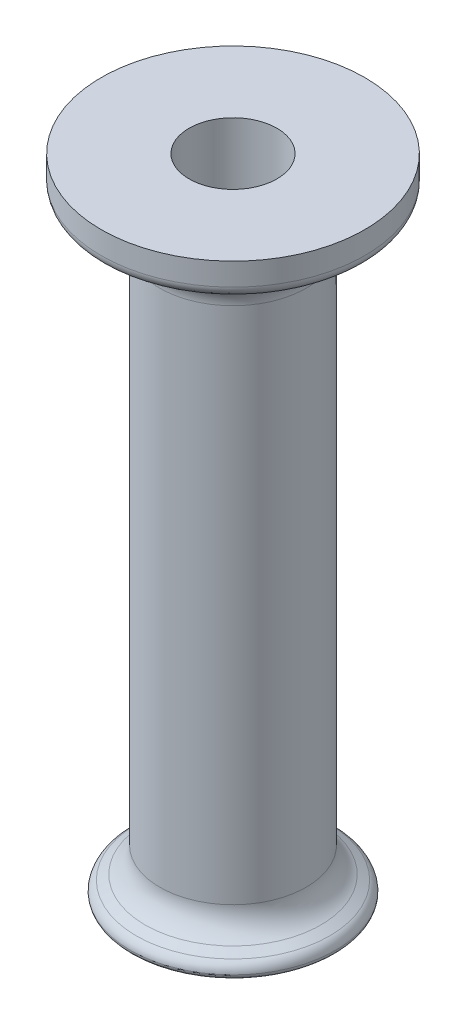
SolidWorks part; units mm, degrees
material "Natural Rubber"
ref_plane "Front Plane" through (0, 0, 0) normal (1, 0, 0) x (0, 1, 0)
ref_plane "Top Plane" through (0, 0, 0) normal (0, 0, 1) x (0, 1, 0)
ref_plane "Right Plane" through (0, 0, 0) normal (0, 1, 0) x (-1, 0, 0)
sketch "Sketch1" plane through (0, 0, 0) normal (1, 0, 0) x (0, 1, 0)
  line L0 (-16.1051, 0) -> (63.2397, 0) construction
  line L1 (0, 25.9687) -> (0, -12.1914) construction
  line L2 (0, 12.5) -> (41.3397, 12.5)
  line L3 (45.6699, 15) -> (50, 22.5)
  line L4 (50, 22.5) -> (55, 22.5)
  line L5 (55, 22.5) -> (55, 7.5)
  line L6 (-55, 7.5) -> (55, 7.5)
  line L7 (55, 0) -> (55, -0.9746)
  line L8 (-51.5566, 15) -> (-52.4226, 16.5)
  line L9 (-54.1547, 17.5) -> (-55, 17.5)
  line L10 (-55, 7.5) -> (-55, 17.5)
  line L11 (0, 12.5) -> (-47.2265, 12.5)
  arc A0 (41.3397, 12.5) -> (45.6699, 15) centre (41.3397, 17.5) ccw
  arc A1 (-47.2265, 12.5) -> (-51.5566, 15) centre (-47.2265, 17.5) cw
  arc A2 (-53.6374, 17.4319) -> (-55, 16.5) centre (-54, 16.5) ccw
  arc A3 (-52.4226, 16.5) -> (-54.1547, 17.5) centre (-54.1547, 15.5) ccw
  point P18 (0, 7.5)
  point P19 (0, 12.5)
  point P25 (-53, 17.5)
  dimension "D1" = 5
  dimension "D8" = 60
  dimension "D10" = 5
  dimension "D11" = 2
  dimension "D12" = 2
  dimension "D13" = 2
  dimension "D2" = 110
  dimension "D3" = 60
  dimension "D4" = 12.5
  dimension "D5" = 15
  dimension "D6" = 15
  dimension "D7" = 5
  dimension "D9" = 10
revolve "Revolve1" add sketch "Sketch1" angle 360 about L0
fillet "Fillet1" radius 2 1 edges at (0, 50, -22.5)
